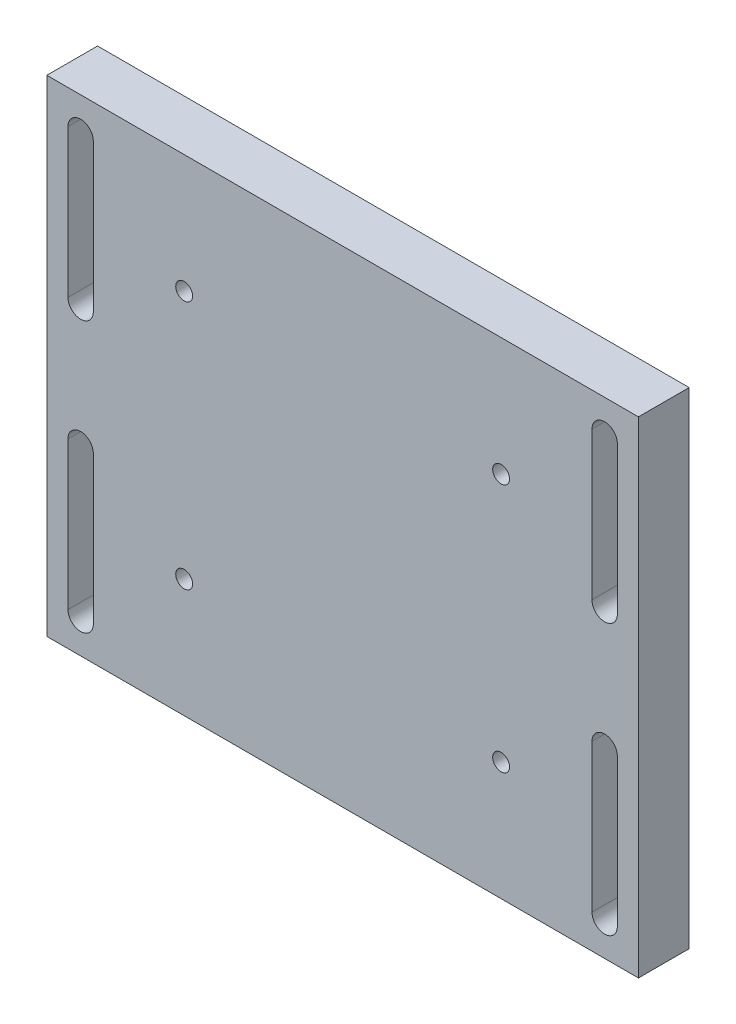
SolidWorks part; units mm, degrees
ref_plane "Front Plane" through (0, 0, 0) normal (0, 0, 1) x (1, 0, 0)
ref_plane "Top Plane" through (0, 0, 0) normal (0, 1, 0) x (1, 0, 0)
ref_plane "Right Plane" through (0, 0, 0) normal (1, 0, 0) x (0, 0, -1)
sketch "Sketch1" plane through (0, 0, 0) normal (0, 0, 1) x (1, 0, 0)
  line L1 (-70, 57.5) -> (70, 57.5)
  line L2 (-70, 57.5) -> (-70, -57.5)
  line L3 (-70, -57.5) -> (70, -57.5)
  line L4 (70, 57.5) -> (70, -57.5)
  line L5 (-70, 57.5) -> (70, -57.5) construction
  line L6 (-70, -57.5) -> (70, 57.5) construction
  point P0 (0, 0)
  dimension "D1" = 115
  dimension "D2" = 140
extrude "Boss-Extrude1" add sketch "Sketch1" along normal mid plane 12
sketch "Sketch4" plane through (0, 0, 6) normal (0, 0, 1) x (1, 0, 0)
  line L0 (70, -57.5) -> (70, 57.5) construction
  line L1 (70, 57.5) -> (-70, 57.5) construction
  line L2 (65, 49.5) -> (65, 14.5)
  line L4 (59, 14.5) -> (59, 49.5)
  arc A0 (65, 49.5) -> (59, 49.5) centre (62, 49.5) ccw
  arc A1 (59, 14.5) -> (65, 14.5) centre (62, 14.5) ccw
  dimension "D1" = 3
  dimension "D3" = 8
  dimension "D5" = 35
  dimension "D2" = 8
extrude "Cut-Extrude1" cut sketch "Sketch4" against normal up to surface (12 mm away) up to face at (0, 0, -6)
sketch "Sketch5" plane through (0, 0, 6) normal (0, 0, 1) x (1, 0, 0)
  line L0 (70, 57.5) -> (-70, 57.5) construction
  circle A0 centre (37.5, 29.5) radius 2
  dimension "D1" = 28
  dimension "D2" = 4
  dimension "D3" = 37.5
extrude "Cut-Extrude2" cut sketch "Sketch5" against normal up to surface (12 mm away) up to face at (62, 32, -6)
mirror "Mirror1" about plane through (0, 0, 0) normal (0, 1, 0) of "Cut-Extrude2", "Cut-Extrude1"
mirror "Mirror2" about plane through (0, 0, 0) normal (1, 0, 0) of "Mirror1", "Cut-Extrude1", "Cut-Extrude2"
